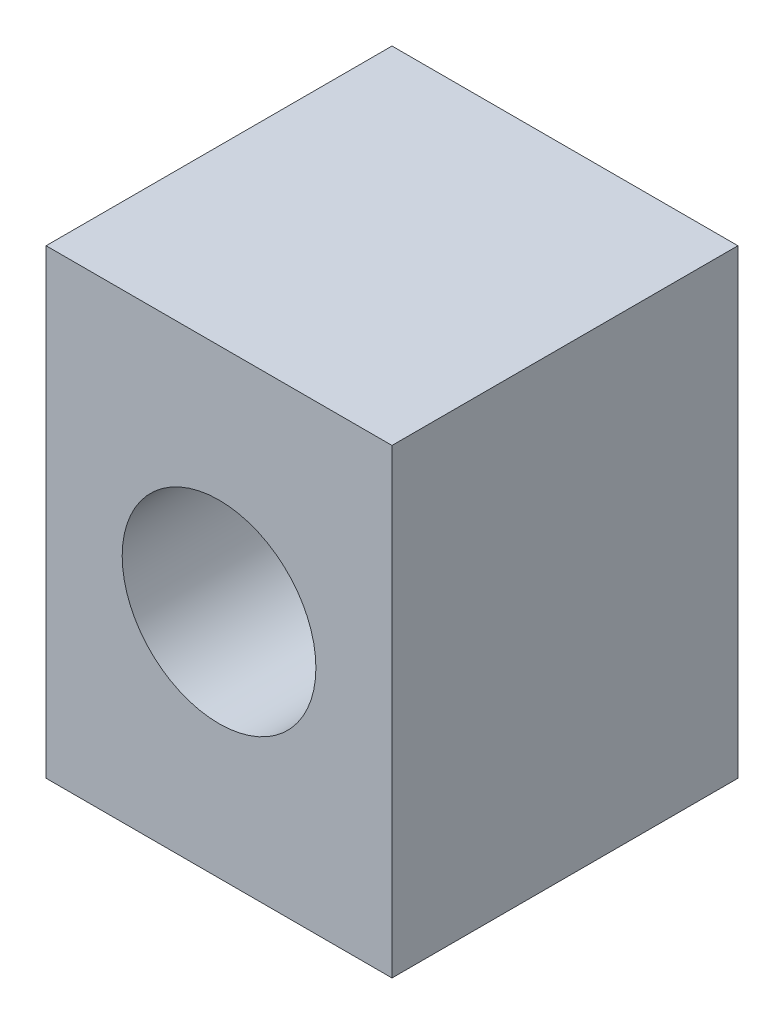
SolidWorks part; units mm, degrees
ref_plane "Front Plane" through (0, 0, 0) normal (0, 0, 1) x (1, 0, 0)
ref_plane "Top Plane" through (0, 0, 0) normal (0, 1, 0) x (1, 0, 0)
ref_plane "Right Plane" through (0, 0, 0) normal (1, 0, 0) x (0, 0, -1)
sketch "Sketch1" plane through (0, 0, 0) normal (0, 0, 1) x (1, 0, 0)
  line L1 (-19.05, -25.4) -> (19.05, -25.4)
  line L2 (-19.05, -25.4) -> (-19.05, 25.4)
  line L3 (-19.05, 25.4) -> (19.05, 25.4)
  line L4 (19.05, -25.4) -> (19.05, 25.4)
  line L5 (-19.05, -25.4) -> (19.05, 25.4) construction
  line L6 (-19.05, 25.4) -> (19.05, -25.4) construction
  circle A0 centre (0, 0) radius 10.668
  point P0 (0, 0)
  dimension "D3" = 21.336
  dimension "D1" = 38.1
  dimension "D2" = 50.8
extrude "Boss-Extrude1" add sketch "Sketch1" along normal blind 38.1
